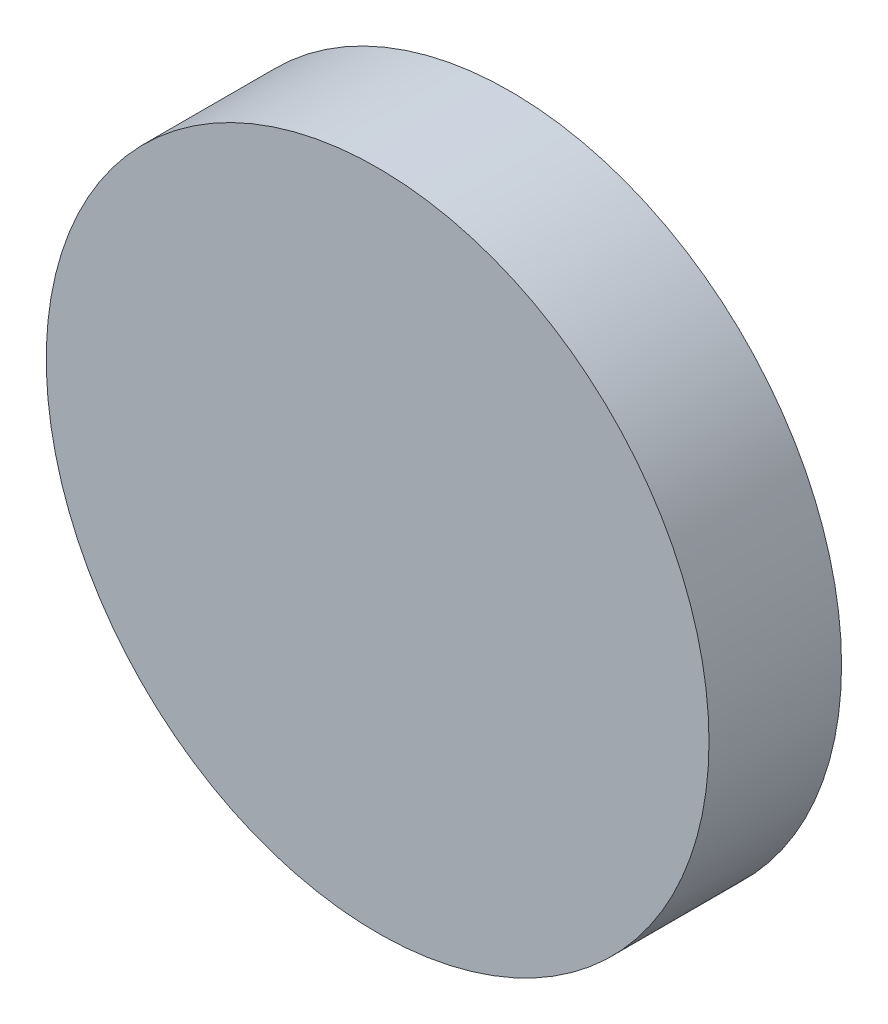
SolidWorks part; units mm, degrees
ref_plane "Front Plane" through (0, 0, 0) normal (0, 0, 1) x (1, 0, 0)
ref_plane "Top Plane" through (0, 0, 0) normal (0, 1, 0) x (1, 0, 0)
ref_plane "Right Plane" through (0, 0, 0) normal (1, 0, 0) x (0, 0, -1)
other "Configuration Table"
sketch "Sketch1" plane through (0, 0, 0) normal (0, 0, 1) x (1, 0, 0)
  circle A0 centre (450, 1805) radius 100
extrude "STORE_sog1_kondenser_fan" add sketch "Sketch1" against normal blind 40 from offset 200 separate body
